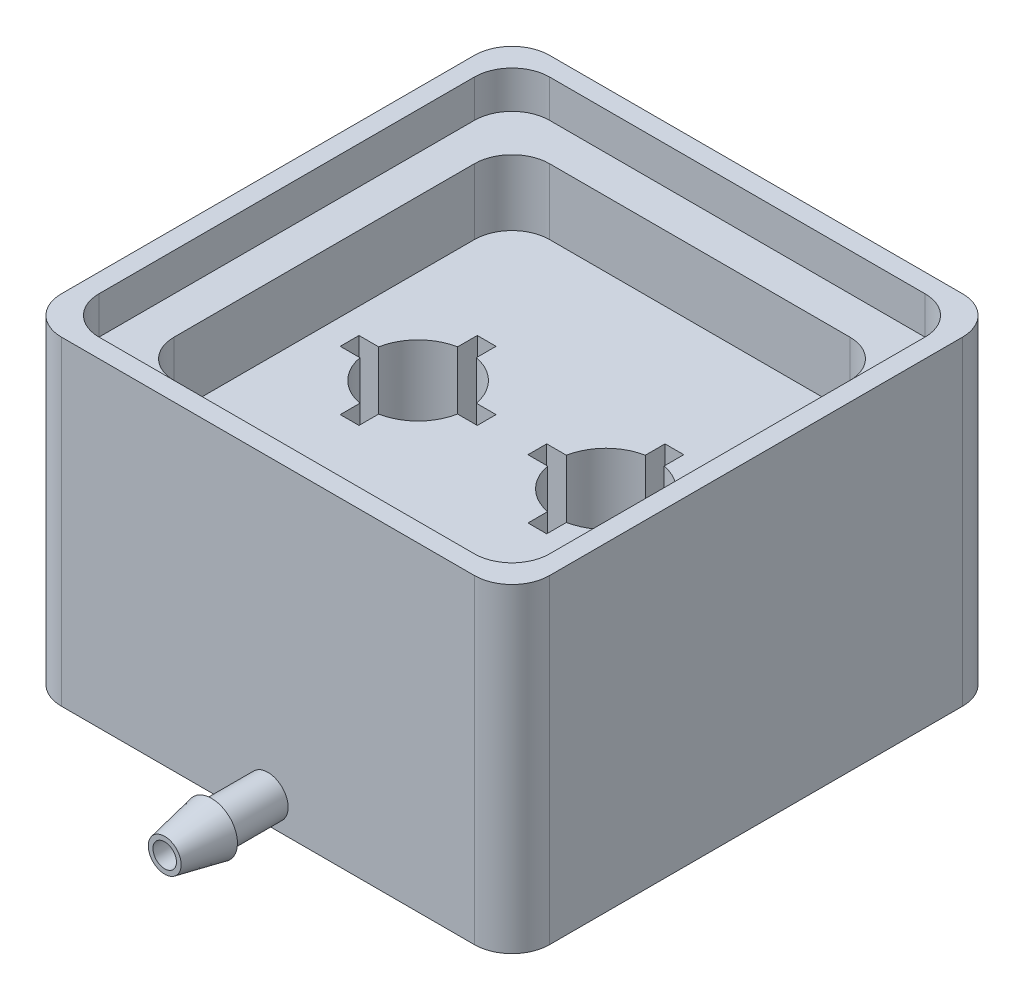
SolidWorks part; units mm, degrees
ref_plane "Front Plane" through (0, 0, 0) normal (0, 0, 1) x (1, 0, 0)
ref_plane "Top Plane" through (0, 0, 0) normal (0, 1, 0) x (1, 0, 0)
ref_plane "Right Plane" through (0, 0, 0) normal (1, 0, 0) x (0, 0, -1)
sketch "Sketch1" plane through (0, 0, 0) normal (0, 1, 0) x (1, 0, 0)
  line L0 (-5, 0) -> (5, 0) construction
  line L1 (-11, -13) -> (11, -13)
  line L2 (-13, -11) -> (-13, 11)
  line L3 (-11, 13) -> (11, 13)
  line L4 (13, -11) -> (13, 11)
  line L5 (-13, -13) -> (13, 13) construction
  line L6 (-13, 13) -> (13, -13) construction
  arc A0 (-13, 11) -> (-11, 13) centre (-11, 11) cw
  arc A1 (11, 13) -> (13, 11) centre (11, 11) cw
  arc A2 (-13, -11) -> (-11, -13) centre (-11, -11) ccw
  arc A3 (13, -11) -> (11, -13) centre (11, -11) cw
  circle A4 centre (5, 0) radius 2.65
  circle A5 centre (-5, 0) radius 2.65
  point P0 (0, 0)
  point P21 (0, 0)
  dimension "D3" = 2
  dimension "D4" = 2
  dimension "D6" = 5.3
  dimension "D7" = 5.3
  dimension "D1" = 26
  dimension "D2" = 26
  dimension "D5" = 10
extrude "Boss-Extrude1" add sketch "Sketch1" along normal blind 11.53
sketch "Sketch2" plane through (0, 11.53, 0) normal (0, 1, 0) x (1, 0, 0)
  line L0 (-5, 0) -> (5, 0) construction
  line L2 (-8.65, -0.5) -> (-1.35, -0.5)
  line L3 (-8.65, -0.5) -> (-8.65, 0.5)
  line L4 (-8.65, 0.5) -> (-1.35, 0.5)
  line L5 (-1.35, -0.5) -> (-1.35, 0.5)
  line L6 (-8.65, -0.5) -> (-1.35, 0.5) construction
  line L7 (-8.65, 0.5) -> (-1.35, -0.5) construction
  line L8 (-5.5, -3.65) -> (-4.5, -3.65)
  line L9 (-5.5, -3.65) -> (-5.5, 3.65)
  line L10 (-5.5, 3.65) -> (-4.5, 3.65)
  line L11 (-4.5, -3.65) -> (-4.5, 3.65)
  line L12 (-5.5, -3.65) -> (-4.5, 3.65) construction
  line L13 (-5.5, 3.65) -> (-4.5, -3.65) construction
  line L14 (4.5, -3.65) -> (5.5, -3.65)
  line L15 (4.5, -3.65) -> (4.5, 3.65)
  line L16 (4.5, 3.65) -> (5.5, 3.65)
  line L17 (5.5, -3.65) -> (5.5, 3.65)
  line L18 (4.5, -3.65) -> (5.5, 3.65) construction
  line L19 (4.5, 3.65) -> (5.5, -3.65) construction
  line L20 (1.35, -0.5) -> (8.65, -0.5)
  line L21 (1.35, -0.5) -> (1.35, 0.5)
  line L22 (1.35, 0.5) -> (8.65, 0.5)
  line L23 (8.65, -0.5) -> (8.65, 0.5)
  line L24 (1.35, -0.5) -> (8.65, 0.5) construction
  line L25 (1.35, 0.5) -> (8.65, -0.5) construction
  point P3 (0, 0)
  circle M15 centre (5, 0) radius 2.65
  circle M16 centre (-5, 0) radius 2.65
  dimension "D1" = 10
  dimension "D2" = 7.3
  dimension "D3" = 7.3
  dimension "D4" = 7.3
  dimension "D5" = 7.3
  dimension "D6" = 1
  dimension "D7" = 1
  dimension "D8" = 1
  dimension "D9" = 1
extrude "Cut-Extrude1" cut sketch "Sketch2" against normal blind 10.785 contours L17 L16 L15 M15 | L20 L23 L22 M15 | L14 L17 L15 M15 | L22 L21 L20 M15 | L2 L5 L4 M16 | L11 L10 L9 M16 | L4 L3 L2 M16 | L8 L11 L9 M16
sketch "Sketch3" plane through (0, 0, 0) normal (1, 0, 0) x (0, 0, -1)
  line L0 (-13, 0.3) -> (-16, 0.3)
  line L1 (-13, 11.53) -> (-13, 0) construction
  line L2 (-16, 0.3) -> (-16, 0)
  line L3 (-16, 0) -> (-18.5, 0.5)
  line L4 (-18.5, 0.5) -> (-18.5, 0.75)
  line L5 (-18.5, 0.75) -> (-13, 0.75)
  line L6 (-13, 0.75) -> (-13, 0.3)
  line L7 (-13, 1.375) -> (-13.6025, 1.375) construction
  line L8 (-11, 0) -> (11, 0) construction
  dimension "D1" = 2.5
  dimension "D2" = 3
  dimension "D3" = 0.875
  dimension "D4" = 1.075
  dimension "D5" = 0.625
  dimension "D6" = 1.375
revolve "Revolve1" add sketch "Sketch3" angle 360 about L7
sketch "Sketch10" plane through (0, 0, 0) normal (1, 0, 0) x (0, 0, -1)
  circle A0 centre (0, 1.375) radius 0.625
extrude "Cut-Extrude3" cut sketch "Sketch10" against normal up to next and the other way up to next
sketch "Sketch5" plane through (0, 0, 13) normal (0, 0, 1) x (1, 0, 0)
  circle A0 centre (0, 1.375) radius 0.625
  dimension "D1" = 1.25
extrude "Cut-Extrude2" cut sketch "Sketch5" against normal up to next
sketch "Sketch6" plane through (0, 11.53, 0) normal (0, 1, 0) x (1, 0, 0)
  line L1 (-11, -13) -> (11, -13)
  line L2 (-13, -11) -> (-13, 11)
  line L3 (-11, 13) -> (11, 13)
  line L4 (13, -11) -> (13, 11)
  line L5 (-13, -13) -> (13, 13) construction
  line L6 (-13, 13) -> (13, -13) construction
  line L7 (-8, -10) -> (8, -10)
  line L8 (-10, -8) -> (-10, 8)
  line L9 (-8, 10) -> (8, 10)
  line L10 (10, -8) -> (10, 8)
  line L11 (-10, -10) -> (10, 10) construction
  line L12 (-10, 10) -> (10, -10) construction
  arc A0 (-13, -11) -> (-11, -13) centre (-11, -11) ccw
  arc A1 (13, -11) -> (11, -13) centre (11, -11) cw
  arc A2 (13, 11) -> (11, 13) centre (11, 11) ccw
  arc A3 (-11, 13) -> (-13, 11) centre (-11, 11) ccw
  arc A4 (-10, -8) -> (-8, -10) centre (-8, -8) ccw
  arc A5 (8, -10) -> (10, -8) centre (8, -8) ccw
  arc A6 (10, 8) -> (8, 10) centre (8, 8) ccw
  arc A7 (-8, 10) -> (-10, 8) centre (-8, 8) ccw
  point P0 (0, 0)
  point P18 (0, 0)
  dimension "D3" = 2
  dimension "D1" = 26
  dimension "D2" = 26
  dimension "D6" = 2
  dimension "D4" = 3
  dimension "D5" = 3
extrude "Boss-Extrude2" add sketch "Sketch6" along normal blind 3.5
sketch "Sketch8" plane through (0, 15.03, 0) normal (0, 1, 0) x (1, 0, 0)
  line L1 (-11, -13) -> (11, -13)
  line L2 (-13, -11) -> (-13, 11)
  line L3 (-11, 13) -> (11, 13)
  line L4 (13, -11) -> (13, 11)
  line L5 (-13, -13) -> (13, 13) construction
  line L6 (-13, 13) -> (13, -13) construction
  line L7 (-10, -12) -> (10, -12)
  line L8 (-12, -10) -> (-12, 10)
  line L9 (-10, 12) -> (10, 12)
  line L10 (12, -10) -> (12, 10)
  line L11 (-12, -12) -> (12, 12) construction
  line L12 (-12, 12) -> (12, -12) construction
  arc A0 (13, 11) -> (11, 13) centre (11, 11) ccw
  arc A1 (13, -11) -> (11, -13) centre (11, -11) cw
  arc A2 (-13, -11) -> (-11, -13) centre (-11, -11) ccw
  arc A3 (-13, 11) -> (-11, 13) centre (-11, 11) cw
  arc A4 (-12, -10) -> (-10, -12) centre (-10, -10) ccw
  arc A5 (10, -12) -> (12, -10) centre (10, -10) ccw
  arc A6 (12, 10) -> (10, 12) centre (10, 10) ccw
  arc A7 (-12, 10) -> (-10, 12) centre (-10, 10) cw
  point P0 (0, 0)
  point P18 (0, 0)
  dimension "D3" = 2
  dimension "D1" = 26
  dimension "D2" = 26
  dimension "D6" = 2
  dimension "D4" = 1
  dimension "D5" = 1
extrude "Boss-Extrude3" add sketch "Sketch8" along normal blind 2
equation "\"D2@Sketch1\"=\"D1@Sketch1\""
equation "\"D7@Sketch1\"=\"D6@Sketch1\""
equation "\"D3@Sketch2\"=\"D2@Sketch2\""
equation "\"D2@Sketch2\"=\"D6@Sketch1\"+2mm"
equation "\"D4@Sketch2\"=\"D2@Sketch2\""
equation "\"D5@Sketch2\"=\"D2@Sketch2\""
equation "\"D7@Sketch2\"=\"D6@Sketch2\""
equation "\"D8@Sketch2\"=\"D6@Sketch2\""
equation "\"D9@Sketch2\"=\"D6@Sketch2\""
equation "\"D1@Sketch6\"=\"D1@Sketch1\""
equation "\"D2@Sketch6\"=\"D1@Sketch1\""
equation "\"D5@Sketch6\"=\"D4@Sketch6\""
equation "\"D1@Sketch8\"=\"D1@Sketch1\""
equation "\"D2@Sketch8\"=\"D1@Sketch1\""
equation "\"D1@Sketch2\"=\"D5@Sketch1\""
